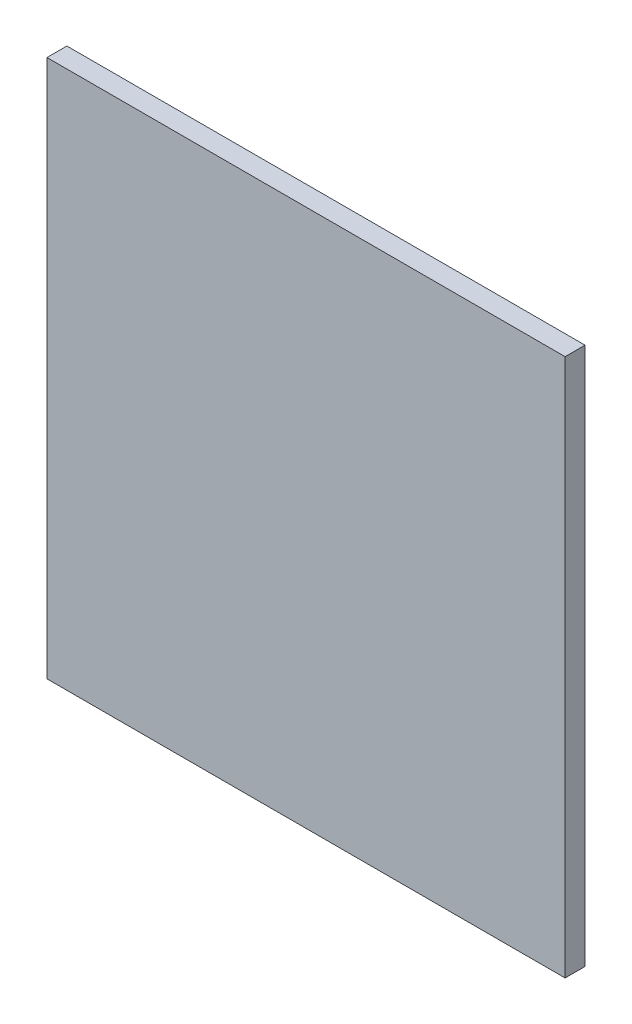
SolidWorks part; units mm, degrees
ref_plane "Front Plane" through (0, 0, 0) normal (0, 0, 1) x (1, 0, 0)
ref_plane "Top Plane" through (0, 0, 0) normal (0, 1, 0) x (1, 0, 0)
ref_plane "Right Plane" through (0, 0, 0) normal (1, 0, 0) x (0, 0, -1)
sketch "Sketch1" plane through (0, 0, 0) normal (0, 0, 1) x (1, 0, 0)
  line L0 (-6.35, 155.575) -> (-6.35, -15.875) construction
  line L1 (158.75, 155.575) -> (-6.35, 155.575)
  line L2 (158.75, 155.575) -> (158.75, -15.875)
  line L3 (158.75, -15.875) -> (-6.35, -15.875)
  line L4 (-6.35, 155.575) -> (-6.35, -15.875)
  line L6 (0, -15.875) -> (-6.35, -15.875) construction
extrude "Boss-Extrude1" add sketch "Sketch1" along normal blind 6.35
